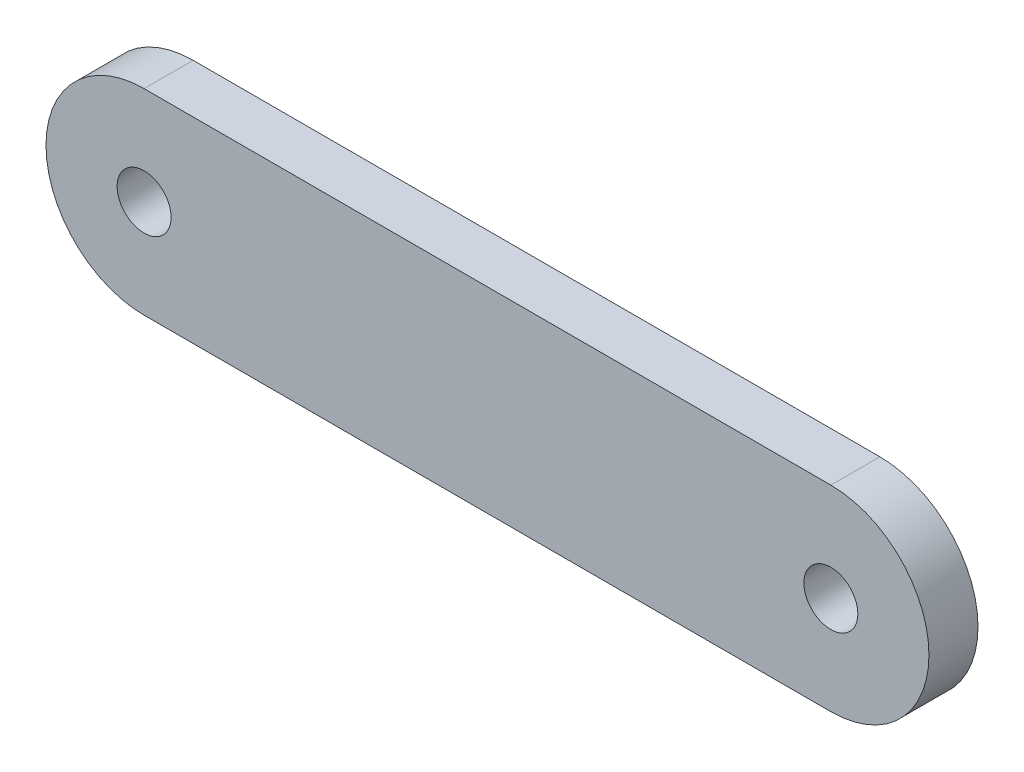
SolidWorks part; units mm, degrees
material "PA Type 6"
ref_plane "Front Plane" through (0, 0, 0) normal (0, 0, 1) x (1, 0, 0)
ref_plane "Top Plane" through (0, 0, 0) normal (0, 1, 0) x (1, 0, 0)
ref_plane "Right Plane" through (0, 0, 0) normal (1, 0, 0) x (0, 0, -1)
sketch "Sketch1" plane through (0, 0, 0) normal (0, 0, 1) x (1, 0, 0)
  line L0 (0, 0) -> (140, 0)
  line L1 (140, 40) -> (0, 40)
  arc A0 (140, 0) -> (140, 40) centre (140, 20) ccw
  arc A1 (0, 40) -> (0, 0) centre (0, 20) ccw
  circle A2 centre (0, 20) radius 5.5
  circle A3 centre (140, 20) radius 5.5
  dimension "D1" = 11
  dimension "D2" = 11
  dimension "D3" = 20
  dimension "D4" = 140
extrude "Boss-Extrude1" add sketch "Sketch1" along normal blind 10
